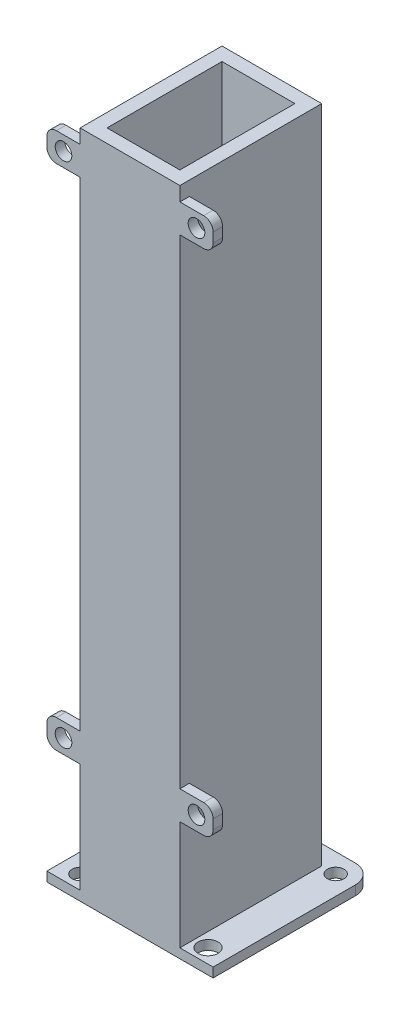
SolidWorks part; units mm, degrees
ref_plane "Plan de face" through (0, 0, 0) normal (0, 0, 1) x (1, 0, 0)
ref_plane "Plan de dessus" through (0, 0, 0) normal (0, 1, 0) x (1, 0, 0)
ref_plane "Plan de droite" through (0, 0, 0) normal (1, 0, 0) x (0, 0, -1)
sketch "Esquisse1" plane through (0, 0, 0) normal (0, 1, 0) x (1, 0, 0)
  line L0 (0, 0) -> (35, 0)
  line L1 (35, 0) -> (35, -35)
  line L2 (0, 0) -> (0, -35)
  line L3 (0, -35) -> (35, -35)
  dimension "D1" = 35
  dimension "D2" = 35
extrude "Boss.-Extru.1" add sketch "Esquisse1" along normal blind 2
sketch "Esquisse2" plane through (0, 2, 0) normal (0, 1, 0) x (1, 0, 0)
  line L0 (0, -33.935) -> (0, -35)
  line L1 (0, -33.935) -> (35, -33.935)
  line L6 (0, 0) -> (0, -35) construction
  line L7 (35, -35) -> (35, 0) construction
  line L8 (0, -35) -> (35, -35)
  line L9 (35, -35) -> (35, -33.935)
  circle A9 centre (30.935, -4.065) radius 1.75
  circle A10 centre (30.935, -30.935) radius 1.75
  circle A11 centre (4.065, -4.065) radius 1.75
  circle A12 centre (4.065, -30.935) radius 1.75
extrude "Enlèv. mat.-Extru.1" cut sketch "Esquisse2" against normal blind 2
sketch "Esquisse4" plane through (0, 2, 0) normal (0, 1, 0) x (1, 0, 0)
  line L0 (17.5, -33.935) -> (7, -33.935)
  line L1 (35, -33.935) -> (0, -33.935) construction
  line L2 (17.5, -33.935) -> (28, -33.935)
  line L3 (7, -4.065) -> (28, -4.065)
  line L4 (7, -33.935) -> (7, -4.065)
  line L5 (28, -4.065) -> (28, -33.935)
extrude "Boss.-Extru.2" add sketch "Esquisse4" along normal blind 280
sketch "Esquisse5" plane through (0, 0, 33.935) normal (0, 0, 1) x (1, 0, 0)
  line L0 (28, 251) -> (28, 257)
  line L1 (7, 282) -> (7, 2) construction
  line L2 (35, 251) -> (35, 257)
  line L3 (28, 282) -> (28, 2) construction
  line L4 (7, 31) -> (0, 31)
  line L5 (7, 25) -> (0, 25)
  line L6 (28, 25) -> (35, 25)
  line L7 (28, 282) -> (28, 257)
  line L8 (28, 257) -> (28, 25)
  line L10 (28, 251) -> (35, 251)
  line L11 (7, 251) -> (7, 257)
  line L12 (0, 31) -> (0, 25)
  line L13 (7, 31) -> (7, 25)
  line L14 (28, 31) -> (35, 31)
  line L15 (35, 31) -> (35, 25)
  line L16 (28, 31) -> (28, 25)
  line L17 (0, 251) -> (0, 257)
  line L18 (28, 257) -> (35, 257)
  line L19 (7, 257) -> (0, 257)
  line L20 (7, 251) -> (0, 251)
  circle A0 centre (3.5, 28) radius 1.75
  circle A1 centre (31.5, 28) radius 1.75
  circle A2 centre (31.5, 254) radius 1.75
  circle A3 centre (3.5, 254) radius 1.75
  line M4 (28, 2) -> (28, 282)
  line M6 (7, 282) -> (7, 2)
extrude "Boss.-Extru.3" add sketch "Esquisse5" against normal blind 2 contours L18 L10 L2 A2 M4 | L20 L19 L17 A3 M6 | L15 L14 L6 A1 M4 | L4 L12 L5 A0 M6
sketch "Esquisse6" plane through (0, 0, 33.935) normal (0, 0, 1) x (1, 0, 0)
  line L7 (0, 144) -> (0, 138)
  line L8 (0, 138) -> (7, 138)
  line L9 (7, 141) -> (7, 138)
  line L10 (7, 141) -> (7, 144)
  line L11 (0, 144) -> (7, 144)
  line L12 (0, 144) -> (0, 141)
  line L13 (0, 144) -> (7, 144)
  line L14 (28, 251) -> (28, 31) construction
  line L15 (28, 144) -> (28, 138)
  line L16 (28, 138) -> (35, 138)
  line L17 (35, 141) -> (35, 138)
  line L18 (35, 141) -> (35, 144)
  line L19 (28, 144) -> (35, 144)
  line L20 (28, 144) -> (28, 141)
  line L21 (0, 144) -> (0, 138)
  line L22 (0, 138) -> (7, 138)
  line L23 (7, 144) -> (7, 138)
  circle A1 centre (3.5, 141) radius 1.75
  circle A2 centre (31.5, 141) radius 1.75
  line M21 (28, 31) -> (28, 251)
  line M31 (7, 251) -> (7, 31)
extrude "Boss.-Extru.4" add sketch "Esquisse6" against normal blind 2 contours L11 L7 L8 A1 M31 | L19 L15 L16 L17 L18 A2 M21
sketch "Esquisse10" plane through (0, 282, 0) normal (0, 1, 0) x (1, 0, 0)
  line L0 (35, -33.935) -> (0, -33.935)
  line L1 (35, -33.935) -> (35, 0)
  line L2 (35, 0) -> (0, 0)
  line L3 (0, -33.935) -> (0, 0)
  circle A0 centre (30.935, -30.935) radius 1.75
  circle A1 centre (30.935, -4.065) radius 1.75
  circle A2 centre (4.065, -4.065) radius 1.75
  circle A3 centre (4.065, -30.935) radius 1.75
extrude "Boss.-Extru.5" add sketch "Esquisse10" against normal blind 2
sketch "Esquisse15" plane through (0, 282, 0) normal (0, 1, 0) x (1, 0, 0)
  circle A0 centre (17.5, -17.5) radius 6.5
  circle A1 centre (30.935, -4.065) radius 1.75
extrude "Enlèv. mat.-Extru.2" cut sketch "Esquisse15" against normal blind 373
fillet "Congé1" radius 2 12 edges at (35, 138, 32.935) (35, 144, 32.935) (35, 25, 32.935) (35, 31, 32.935) (0, 31, 32.935) (0, 25, 32.935) (0, 138, 32.935) (0, 144, 32.935) (0, 251, 32.935) (0, 257, 32.935) (35, 251, 32.935) (35, 257, 32.935)
fillet "Congé2" radius 4 4 edges at (0, 1, 0) (35, 1, 0) (0, 281, 0) (35, 281, 0)
sketch "Esquisse17" plane through (0, 0, 33.935) normal (0, 0, 1) x (1, 0, 0)
  line L0 (7, 144) -> (7, 138)
  line L1 (7, 138) -> (2, 138)
  line L2 (7, 144) -> (2, 144)
  line L3 (28, 144) -> (28, 138)
  line L4 (28, 138) -> (33, 138)
  line L5 (28, 144) -> (33, 144)
  line L6 (35, 142) -> (35, 140)
  line L7 (0, 142) -> (0, 140)
  line L8 (7, 150) -> (7, 144)
  line L9 (7, 144) -> (2, 144)
  line L10 (7, 150) -> (2, 150)
  line L11 (28, 150) -> (28, 144)
  line L12 (28, 144) -> (33, 144)
  line L13 (28, 150) -> (33, 150)
  line L14 (35, 148) -> (35, 146)
  line L15 (0, 148) -> (0, 146)
  line L16 (7, 138) -> (7, 132)
  line L17 (7, 132) -> (2, 132)
  line L18 (7, 138) -> (2, 138)
  line L19 (28, 138) -> (28, 132)
  line L20 (28, 132) -> (33, 132)
  line L21 (28, 138) -> (33, 138)
  line L22 (35, 136) -> (35, 134)
  line L23 (0, 136) -> (0, 134)
  arc A0 (0, 142) -> (2, 144) centre (2, 142) cw
  arc A2 (0, 140) -> (2, 138) centre (2, 140) ccw
  arc A3 (33, 144) -> (35, 142) centre (33, 142) cw
  arc A4 (35, 140) -> (33, 138) centre (33, 140) cw
  circle A5 centre (3.5, 141) radius 1.75
  circle A6 centre (31.5, 141) radius 1.75
  circle A7 centre (31.5, 141) radius 1.75
  arc A8 (0, 148) -> (2, 150) centre (2, 148) cw
  arc A9 (0, 146) -> (2, 144) centre (2, 146) ccw
  arc A10 (33, 150) -> (35, 148) centre (33, 148) cw
  arc A11 (35, 146) -> (33, 144) centre (33, 146) cw
  circle A12 centre (3.5, 147) radius 1.75
  circle A13 centre (31.5, 147) radius 1.75
  circle A14 centre (31.5, 147) radius 1.75
  arc A15 (0, 136) -> (2, 138) centre (2, 136) cw
  arc A16 (0, 134) -> (2, 132) centre (2, 134) ccw
  arc A17 (33, 138) -> (35, 136) centre (33, 136) cw
  arc A18 (35, 134) -> (33, 132) centre (33, 134) cw
  circle A19 centre (3.5, 135) radius 1.75
  circle A20 centre (31.5, 135) radius 1.75
  circle A21 centre (31.5, 135) radius 1.75
extrude "Boss.-Extru.6" add sketch "Esquisse17" against normal blind 2 contours L15 A9 L2 L8 L10 A8 A12 | L23 A16 L17 L16 L1 A15 A19 | A18 L22 A17 L4 L19 L20 A20 | A11 L14 A10 L13 L11 L5 A13
sketch "Esquisse18" plane through (0, 0, 33.935) normal (0, 0, 1) x (1, 0, 0)
  line L3 (2, 138) -> (7, 138)
  line L4 (7, 138) -> (7, 144)
  line L5 (2, 144) -> (7, 144)
  line L6 (37.3625, 138) -> (33, 138)
  line L9 (2, 144) -> (-2.3625, 144)
  line L10 (-2.3625, 144) -> (-2.3625, 138)
  line L11 (-2.3625, 138) -> (2, 138)
  line L12 (37.3625, 144) -> (37.3625, 138)
  line L13 (33, 144) -> (37.3625, 144)
  line L14 (33, 144) -> (28, 144)
  line L15 (28, 138) -> (28, 144)
  line L16 (33, 138) -> (28, 138)
extrude "Enlèv. mat.-Extru.3" cut sketch "Esquisse18" against normal blind 2
sketch "Esquisse19" plane through (0, 0, 4.065) normal (0, 0, -1) x (-1, 0, 0)
  line L0 (-28, 141) -> (-7, 141)
  line L1 (-28, 280) -> (-28, 2) construction
  line L2 (-7, 280) -> (-7, 2) construction
  line L3 (-7, 141) -> (34.5369, 141)
  line L4 (34.5369, 141) -> (34.5369, 293.6482)
  line L5 (34.5369, 293.6482) -> (-77.4519, 293.6482)
  line L6 (-77.4519, 293.6482) -> (-77.4519, 143.9057)
  line L7 (-77.4519, 143.9057) -> (-28, 141)
extrude "Enlèv. mat.-Extru.4" cut sketch "Esquisse19" against normal blind 391 and the other way blind 279
sketch "Esquisse20" plane through (0, 141, 0) normal (0, 1, 0) x (1, 0, 0)
  line L5 (9.8284, -6.8934) -> (25.1716, -6.8934)
  line L6 (9.8284, -6.8934) -> (9.8284, -31.1066)
  line L7 (9.8284, -31.1066) -> (25.1716, -31.1066)
  line L8 (25.1716, -6.8934) -> (25.1716, -31.1066)
extrude "Enlèv. mat.-Extru.5" cut sketch "Esquisse20" against normal blind 20
sketch "Esquisse23" plane through (0, 2, 0) normal (0, 1, 0) x (1, 0, 0)
  circle A0 centre (4.065, -4.065) radius 2.1
  circle A1 centre (4.065, -30.935) radius 2.1
  circle A2 centre (30.935, -30.935) radius 2.1
  circle A4 centre (30.935, -4.065) radius 2.1
extrude "Enlèv. mat.-Extru.6" cut sketch "Esquisse23" against normal blind 10 contours A2
